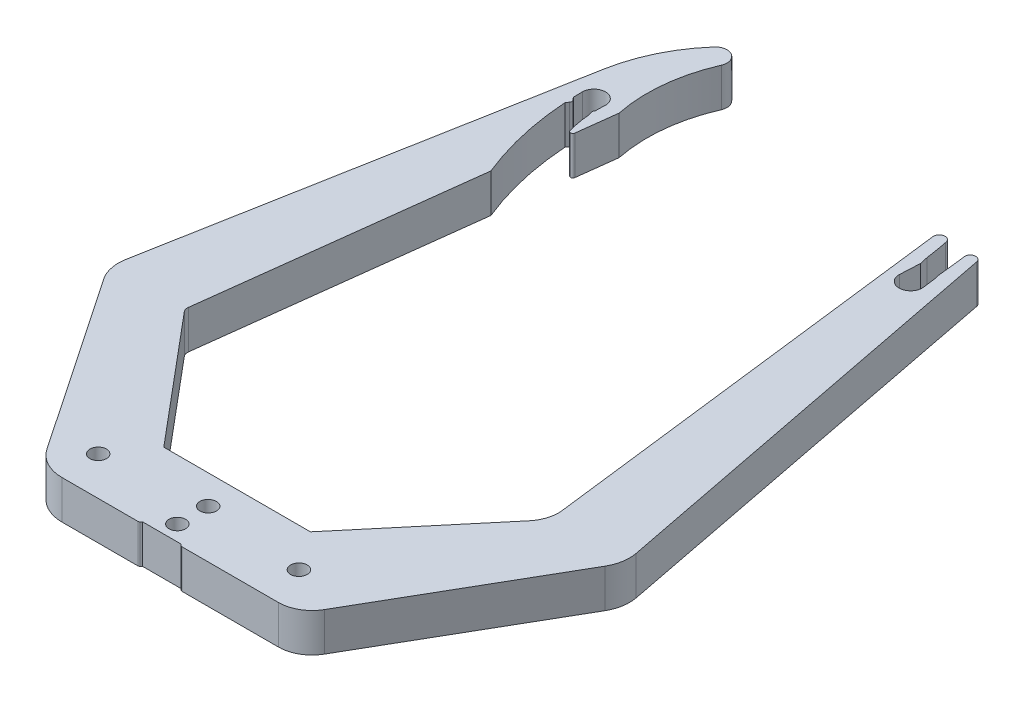
SolidWorks part; units mm, degrees
ref_plane "前视基准面" through (0, 0, 0) normal (0, 0, 1) x (1, 0, 0)
ref_plane "上视基准面" through (0, 0, 0) normal (0, 1, 0) x (1, 0, 0)
ref_plane "右视基准面" through (0, 0, 0) normal (1, 0, 0) x (0, 0, -1)
sketch "草图1" plane through (0, 0, 0) normal (0, 1, 0) x (1, 0, 0)
  line L0 (0, 0) -> (0, -20) construction
  line L1 (-19, 0) -> (19, 0)
  line L2 (-35.7227, -20) -> (35.7227, -20) construction
  line L3 (19, 0) -> (44.8546, 30.8123)
  line L4 (46.8223, 37.4552) -> (33.3895, 146.8562)
  line L5 (38.2306, -15.6563) -> (64.8605, 30.468)
  line L6 (66.0165, 37.3761) -> (44.728, 146.8959)
  line L7 (-5, -19.5) -> (5, -19.5)
  line L8 (5, -19.5) -> (5.3536, -19.8536)
  line L9 (5.7071, -20) -> (30.7071, -20)
  line L10 (-5, -19.5) -> (-5.3536, -19.8536)
  line L11 (-5.7071, -20) -> (-25.3998, -20)
  line L12 (-35.7227, -20) -> (-64.8605, 30.468) construction
  line L13 (-19, 0) -> (-46.7237, 33.0398)
  line L14 (-47.2827, 33.706) -> (-33.3895, 146.8562) construction
  line L15 (-66.0165, 37.3761) -> (-46.8296, 141.8909)
  line L18 (-34.9739, 133.9531) -> (-47.1767, 34.5691)
  line L44 (-64.8605, 30.468) -> (-33.6816, -15.6046)
  line L45 (43.5031, 134.5037) -> (43.077, 137.8137)
  line L46 (42.1293, 145.1753) -> (42.8054, 138.9383)
  line L47 (42.8076, 138.9256) -> (43.077, 137.8137)
  line L48 (37.3208, 141.4732) -> (37.8151, 139.2584)
  line L49 (42.1293, 145.1753) -> (41.9652, 146.45)
  line L50 (37.8174, 139.2316) -> (37.5579, 134.1048)
  arc A0 (64.8605, 30.468) -> (66.0165, 37.3761) centre (56.2002, 35.468) ccw
  arc A1 (-64.8605, 30.468) -> (-66.0165, 37.3761) centre (-56.2002, 35.468) cw
  arc A2 (33.3895, 146.8562) -> (36.3769, 147.1048) centre (34.8784, 147.039) cw
  arc A4 (37.5579, 134.1048) -> (43.5031, 134.5037) centre (40.5541, 133.9531) ccw
  arc A5 (44.728, 146.8959) -> (41.9652, 146.45) centre (43.3537, 146.6287) ccw
  arc A7 (-46.8296, 141.8909) -> (-37.4802, 161.1337) centre (-7.4871, 134.6684) cw
  arc A8 (-37.4802, 161.1337) -> (-32.4793, 157.9531) centre (-35.2307, 159.1488) cw
  arc A9 (-32.4793, 157.9531) -> (-34.9739, 133.9531) centre (4.2063, 142.0103) ccw
  arc A10 (-46.7237, 33.0398) -> (-47.1767, 34.5691) centre (-45.1916, 34.3254) cw
  arc A19 (38.2306, -15.6563) -> (30.7071, -20) centre (30.7071, -11.3127) cw
  arc A20 (44.8546, 30.8123) -> (46.8223, 37.4552) centre (38.1997, 36.3964) ccw
  arc A21 (5.3536, -19.8536) -> (5.7071, -20) centre (5.7071, -19.5) ccw
  arc A22 (-5.3536, -19.8536) -> (-5.7071, -20) centre (-5.7071, -19.5) cw
  arc A34 (-25.3998, -20) -> (-33.6816, -15.6046) centre (-25.3998, -10) cw
  arc A37 (42.8054, 138.9383) -> (42.8076, 138.9256) centre (42.9048, 138.9491) ccw
  arc A38 (37.8151, 139.2584) -> (37.8174, 139.2316) centre (37.7175, 139.2366) cw
  arc A39 (36.3769, 147.1048) -> (37.3208, 141.4732) centre (-54.0014, 129.0619) cw
  point P7 (0, 0)
  point P9 (0, -20)
  point P18 (66.7299, 33.706)
  point P24 (0, -19.5)
  point P43 (-30.7071, -20)
  point P50 (46.8296, 141.8909)
  point P53 (42.8061, 138.9319)
  point P76 (-42.7886, -7.7616)
  point P85 (47.2827, 33.706)
  point P88 (5.5, -20)
  point P91 (-5.5, -20)
  dimension "D14" = 10
  dimension "D17" = 1.5
  dimension "D18" = 3
  dimension "1.4" = 1.4
  dimension "D23" = 40
  dimension "D24" = 3
  dimension "D26" = 40
  dimension "D30" = 2
  dimension "D39" = 0.5
  dimension "D28" = 10
  dimension "D15" = 4.8
  dimension "D16" = 0.1
  dimension "D1" = 20
  dimension "D2" = 38
  dimension "D4" = 130
  dimension "D5" = 44
  dimension "D6" = 133
  dimension "D7" = 114
  dimension "D8" = 120
  dimension "D9" = 139
  dimension "D10" = 110
  dimension "D11" = 5
  dimension "D12" = 1
  dimension "D13" = 135
  dimension "D19" = 13
  dimension "D25" = 13
  dimension "D27" = 24
  dimension "D29" = 25
  dimension "D31" = 25
extrude "凸台-拉伸1" add sketch "草图1" along normal blind 10
sketch "草图2" plane through (0, 10, 0) normal (0, 1, 0) x (1, 0, 0)
  line L0 (-47.1767, 34.5691) -> (-34.9739, 133.9531) construction
  line L2 (-36.5496, 121.12) -> (-38.6077, 104.3574)
  line L3 (-5, -19.5) -> (5, -19.5) construction
  line L4 (-38.7444, 130.4462) -> (-38.4867, 129.7939)
  line L9 (40.5541, 133.9531) -> (-57.9515, 133.9531) construction
  line L10 (0, 0) -> (0, -21.5487) construction
  line L11 (-38.5563, 131.3155) -> (-38.5461, 131.3251)
  line L12 (-44.4474, 131.5436) -> (-43.9248, 131.0031)
  line L13 (-43.8451, 129.9874) -> (-44.3325, 129.293)
  line L14 (38.654, -10) -> (-42.7555, -10) construction
  line L15 (19, 0) -> (-19, 0) construction
  arc A0 (-38.6077, 104.3574) -> (-44.3325, 129.293) centre (35.4981, 134.4958) cw
  circle A3 centre (0, -15.5) radius 2.15
  circle A4 centre (0, -7.5) radius 2.15
  arc A7 (-38.5057, 133.7686) -> (-38.5563, 131.3155) centre (-8.5625, 131.9238) ccw
  arc A13 (-38.5057, 133.7686) -> (-44.4999, 133.932) centre (-41.5, 133.9531) ccw
  arc A14 (-44.4474, 131.5436) -> (-44.4999, 133.932) centre (35.4981, 134.4958) cw
  arc A15 (-38.4867, 129.7939) -> (-36.5496, 121.12) centre (-8.5625, 131.9238) ccw
  arc A16 (-38.5461, 131.3251) -> (-38.7444, 130.4462) centre (-38.0003, 130.7401) ccw
  arc A17 (-43.9248, 131.0031) -> (-43.8451, 129.9874) centre (-44.4999, 130.447) cw
  circle A18 centre (-26, -10) radius 2.15
  circle A19 centre (26, -10) radius 2.15
  point P30 (-38.9446, 130.9532)
  point P32 (-38.4181, 119.1092)
  point P34 (-43.4656, 130.5282)
  dimension "D5" = 3
  dimension "D6" = 30
  dimension "D7" = 80
  dimension "D9" = 4.3
  dimension "D11" = 26
  dimension "D12" = 0.8
  dimension "D14" = 10
  dimension "D2" = 4.3
  dimension "D3" = 4.3
  dimension "D4" = 41.5
  dimension "D8" = 8
  dimension "D10" = 4
  dimension "D13" = 26
extrude "切除-拉伸1" cut sketch "草图2" against normal up to next
fillet "圆角1" radius 0.6 2 edges at (-34.9739, 5, -133.9531) (-36.5496, 5, -121.12)
